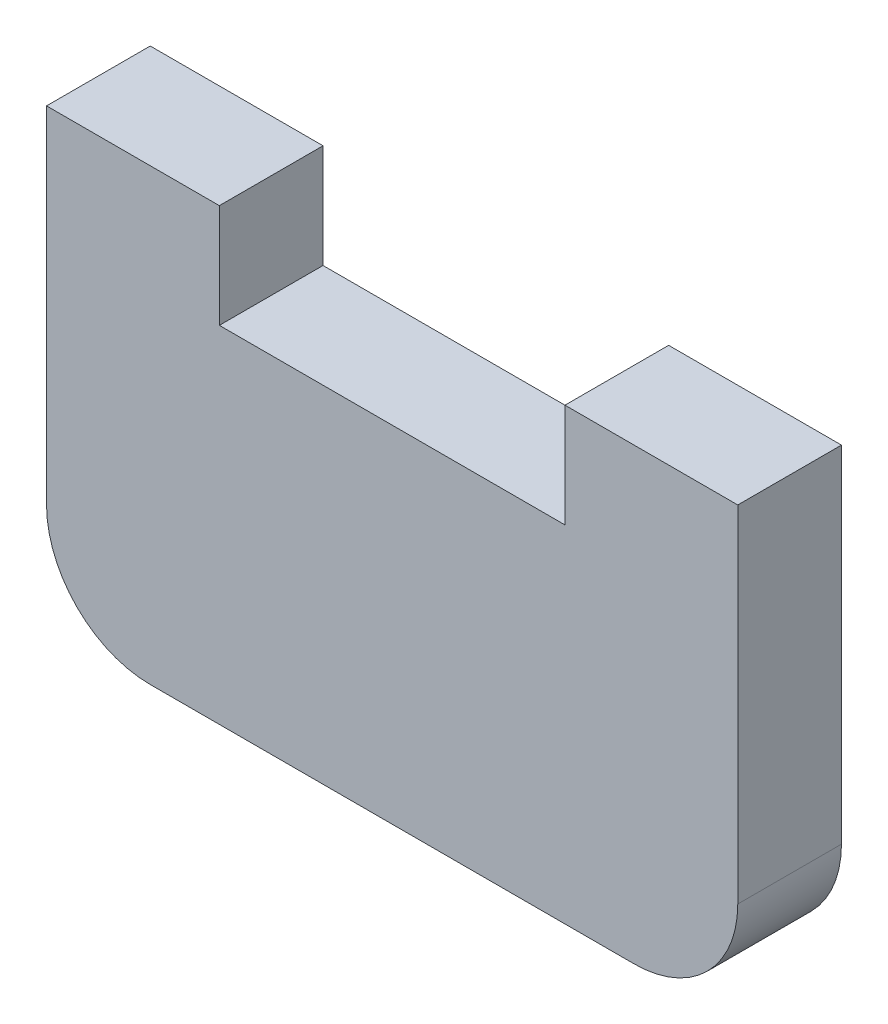
SolidWorks part; units mm, degrees
ref_plane "Alzado" through (0, 0, 0) normal (0, 0, 1) x (1, 0, 0)
ref_plane "Planta" through (0, 0, 0) normal (0, 1, 0) x (1, 0, 0)
ref_plane "Vista lateral" through (0, 0, 0) normal (1, 0, 0) x (0, 0, -1)
sketch "Croquis1" plane through (0, 0, 0) normal (0, 0, 1) x (1, 0, 0)
  line L0 (0, 22.001) -> (-5, 22.001)
  line L1 (-5, 22.001) -> (-5, 12.001)
  line L2 (-2, 9.001) -> (12, 9.001)
  line L3 (15, 12.001) -> (15, 22.001)
  line L4 (15, 22.001) -> (10, 22.001)
  line L5 (10, 22.001) -> (10, 19.001)
  line L6 (10, 19.001) -> (0, 19.001)
  line L12 (0, 19.001) -> (0, 22.001)
  arc A0 (12, 9.001) -> (15, 12.001) centre (12, 12.001) ccw
  arc A1 (-5, 12.001) -> (-2, 9.001) centre (-2, 12.001) ccw
  dimension "D1" = 3
extrude "Saliente-Extruir1" add sketch "Croquis1" along normal blind 3
